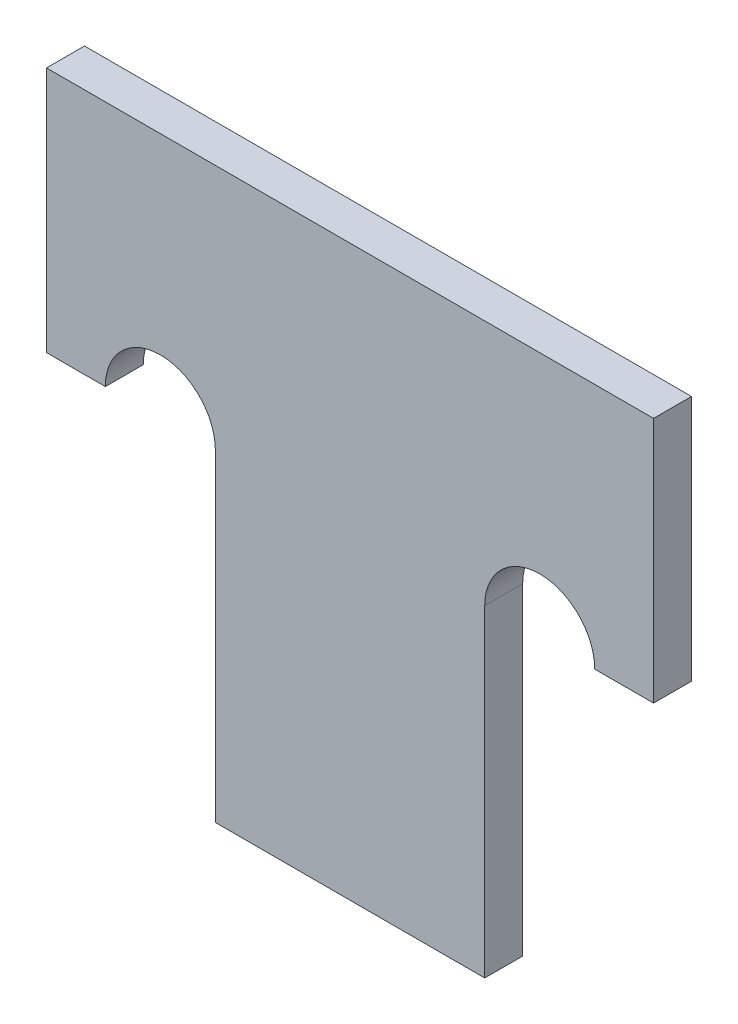
SolidWorks part; units mm, degrees
material "7075-T6 (SN)"
ref_plane "Front Plane" through (0, 0, 0) normal (0, 0, 1) x (1, 0, 0)
ref_plane "Top Plane" through (0, 0, 0) normal (0, 1, 0) x (1, 0, 0)
ref_plane "Right Plane" through (0, 0, 0) normal (1, 0, 0) x (0, 0, -1)
sketch "Sketch1" plane through (0, 0, 0) normal (0, 0, 1) x (1, 0, 0)
  line L0 (-20.32, 2.54) -> (20.32, 2.54) construction
  line L1 (-20.32, -19.05) -> (20.32, -19.05)
  line L2 (-20.32, -19.05) -> (-20.32, 19.05)
  line L3 (-20.32, 19.05) -> (20.32, 19.05)
  line L4 (20.32, -19.05) -> (20.32, 19.05)
  line L5 (-20.32, -19.05) -> (20.32, 19.05) construction
  line L6 (-20.32, 19.05) -> (20.32, -19.05) construction
  line L7 (0, 5.8923) -> (0, -3.1789) construction
  circle A0 centre (12.7, 2.54) radius 3.175
  circle A1 centre (-12.7, 2.54) radius 3.175
  point P0 (0, 0)
  dimension "D5" = 6.35
  dimension "D1" = 25.4
  dimension "D3" = 38.1
  dimension "D4" = 16.51
  dimension "D6" = 40.64
extrude "Boss-Extrude1" add sketch "Sketch1" along normal blind 2.54
sketch "Sketch2" plane through (0, 0, 0) normal (0, 0, 1) x (1, 0, 0)
  line L0 (0, -10.4784) -> (0, 10.4784) construction
  line L1 (9.017, 2.54) -> (9.017, -19.05)
  line L2 (-20.32, -19.05) -> (20.32, -19.05) construction
  line L4 (16.383, 2.54) -> (20.32, 2.54)
  line L6 (-9.017, 2.54) -> (-9.017, -19.05)
  line L20 (20.32, -19.05) -> (20.32, 19.05) construction
  line L22 (-16.383, 2.54) -> (-20.32, 2.54)
  line L23 (-20.32, 19.05) -> (-20.32, -19.05) construction
  line L24 (-20.32, 2.54) -> (-20.32, -19.05)
  line L25 (-20.32, -19.05) -> (-9.017, -19.05)
  line L26 (20.32, -19.05) -> (20.32, 2.54)
  line L27 (9.017, -19.05) -> (20.32, -19.05)
  arc A0 (16.383, 2.54) -> (9.017, 2.54) centre (12.7, 2.54) ccw
  circle A1 centre (12.7, 2.54) radius 3.175 construction
  arc A2 (-16.383, 2.54) -> (-9.017, 2.54) centre (-12.7, 2.54) cw
  dimension "D1" = 0.508
extrude "Cut-Extrude1" cut sketch "Sketch2" along normal up to surface (2.54 mm away) up to face at (0, 0, 2.54)
